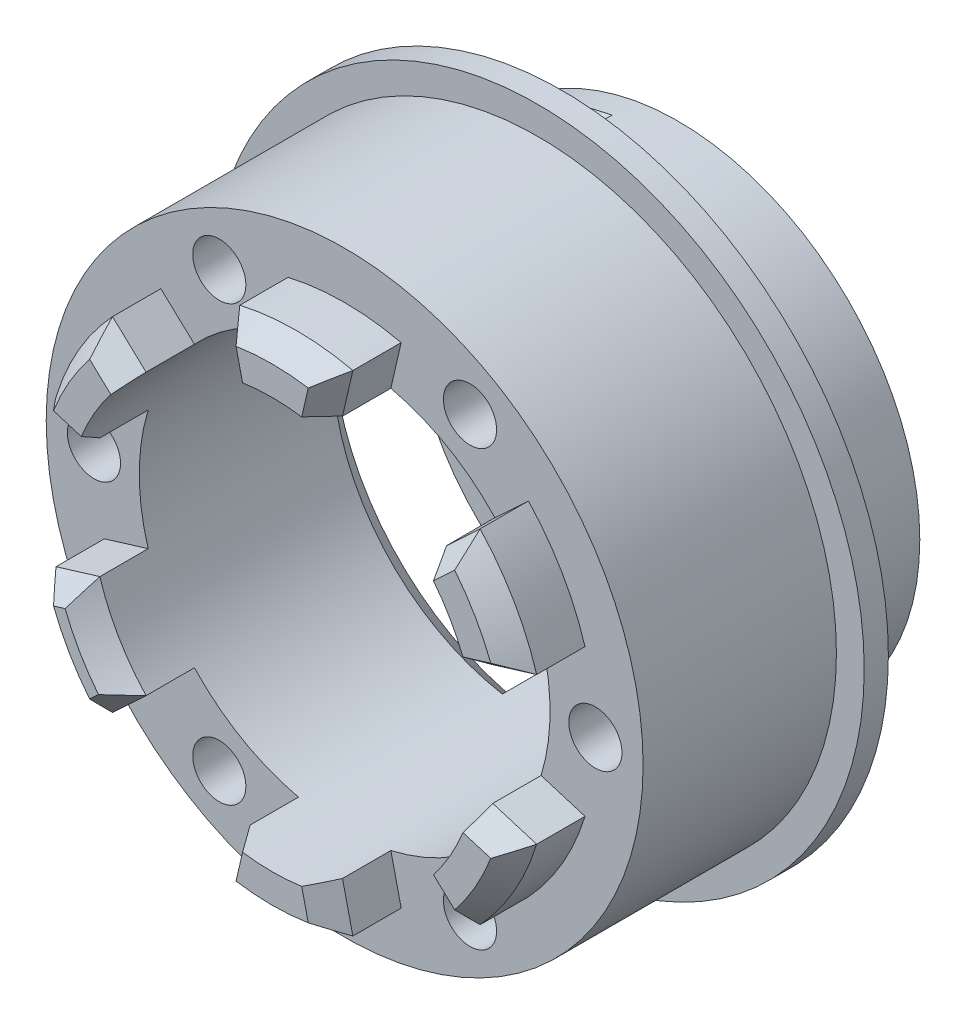
SolidWorks part; units mm, degrees
ref_plane "정면" through (0, 0, 0) normal (0, 0, 1) x (1, 0, 0)
ref_plane "윗면" through (0, 0, 0) normal (0, 1, 0) x (1, 0, 0)
ref_plane "우측면" through (0, 0, 0) normal (1, 0, 0) x (0, 0, -1)
sketch "스케치1" plane through (0, 0, 0) normal (0, 0, 1) x (1, 0, 0)
  circle A0 centre (0, 0) radius 10
  dimension "D1" = 20
extrude "보스-돌출1" add sketch "스케치1" along normal blind 2
sketch "스케치2" plane through (0, 0, 2) normal (0, 0, 1) x (1, 0, 0)
  circle A0 centre (0, 0) radius 10
  circle A1 centre (0, 0) radius 8.5
  circle A5 centre (0, 0) radius 10 construction
  dimension "D1" = 1.5
extrude "보스-돌출2" add sketch "스케치2" along normal blind 2.8
sketch "스케치4" plane through (0, 0, 4.8) normal (0, 0, 1) x (1, 0, 0)
  circle A0 centre (0, 0) radius 13.5
  circle A1 centre (0, 0) radius 8.5
  circle A2 centre (0, 0) radius 8.5 construction
  dimension "D1" = 27
extrude "보스-돌출3" add sketch "스케치4" along normal blind 1
sketch "스케치5" plane through (0, 0, 5.8) normal (0, 0, 1) x (1, 0, 0)
  circle A0 centre (0, 0) radius 8.5
  circle A1 centre (0, 0) radius 12.35
  circle A2 centre (0, 0) radius 8.5 construction
  dimension "D1" = 24.7
extrude "보스-돌출4" add sketch "스케치5" along normal blind 8
sketch "스케치6" plane through (0, 0, 13.8) normal (0, 0, 1) x (1, 0, 0)
  circle A0 centre (0, 0) radius 10.375 construction
  circle A6 centre (0, 0) radius 8.5 construction
  circle A8 centre (10.375, 0) radius 1.1
  circle A9 centre (5.1875, -8.985) radius 1.1
  circle A10 centre (-5.1875, -8.985) radius 1.1
  circle A11 centre (-10.375, 0) radius 1.1
  circle A12 centre (-5.1875, 8.985) radius 1.1
  circle A13 centre (5.1875, 8.985) radius 1.1
  point P19 (0, 0)
  point P20 (0, 0)
  dimension "D1" = 1.875
  dimension "D2" = 2.2
  dimension "D3" = 6
extrude "컷-돌출1" cut sketch "스케치6" against normal blind 8
sketch "스케치7" plane through (0, 0, 0) normal (0, 0, -1) x (-1, 0, 0)
  circle A0 centre (0, 0) radius 7 construction
  circle A5 centre (0, 0) radius 3
  circle A6 centre (-7, 0) radius 1.15
  circle A7 centre (7, 0) radius 1.15
  circle A9 centre (0, 7) radius 1.15
  circle A11 centre (0, -7) radius 1.15
  dimension "D1" = 14
  dimension "D2" = 2.3
  dimension "D4" = 6
extrude "컷-돌출2" cut sketch "스케치7" against normal through all
sketch "스케치10" plane through (0, 0, 13.8) normal (0, 0, 1) x (1, 0, 0)
  line L24 (2.3395, 10.1334) -> (1.9121, 8.2821)
  line L25 (-2.3395, 10.1334) -> (-1.9121, 8.2821)
  line L26 (7.6061, 7.0928) -> (6.2165, 5.797)
  line L27 (9.9456, 3.0407) -> (8.1286, 2.4852)
  line L28 (9.9456, -3.0407) -> (8.1286, -2.4852)
  line L29 (7.6061, -7.0928) -> (6.2165, -5.797)
  line L30 (2.3395, -10.1334) -> (1.9121, -8.2821)
  line L31 (-2.3395, -10.1334) -> (-1.9121, -8.2821)
  line L32 (-7.6061, -7.0928) -> (-6.2165, -5.797)
  line L33 (-9.9456, -3.0407) -> (-8.1286, -2.4852)
  line L34 (-9.9456, 3.0407) -> (-8.1286, 2.4852)
  line L35 (-7.6061, 7.0928) -> (-6.2165, 5.797)
  arc A0 (-7.6061, 7.0928) -> (-9.9456, 3.0407) centre (0, 0) ccw
  arc A1 (-8.1286, -2.4852) -> (-6.2165, -5.797) centre (0, 0) ccw
  arc A2 (2.3395, 10.1334) -> (-2.3395, 10.1334) centre (0, 0) ccw
  arc A3 (9.9456, 3.0407) -> (7.6061, 7.0928) centre (0, 0) ccw
  arc A4 (7.6061, -7.0928) -> (9.9456, -3.0407) centre (0, 0) ccw
  arc A5 (-2.3395, -10.1334) -> (2.3395, -10.1334) centre (0, 0) ccw
  arc A6 (-9.9456, -3.0407) -> (-7.6061, -7.0928) centre (0, 0) ccw
  arc A7 (-1.9121, -8.2821) -> (1.9121, -8.2821) centre (0, 0) ccw
  arc A8 (6.2165, -5.797) -> (8.1286, -2.4852) centre (0, 0) ccw
  arc A9 (8.1286, 2.4852) -> (6.2165, 5.797) centre (0, 0) ccw
  arc A10 (1.9121, 8.2821) -> (-1.9121, 8.2821) centre (0, 0) ccw
  arc A11 (-6.2165, 5.797) -> (-8.1286, 2.4852) centre (0, 0) ccw
  circle A12 centre (0, 0) radius 8.5 construction
  circle A13 centre (0, 0) radius 8.5 construction
  point P9 (0, 0)
  point P10 (0, 0)
  point P21 (0, 0)
  point P30 (0, 0)
  point P48 (0, 0)
  point P61 (0, 0)
  dimension "D1" = 1.9
  dimension "D4" = 6
extrude "보스-돌출5" add sketch "스케치10" along normal blind 3
chamfer "모따기1" distance 1 angle 35 19 edges at (-9.0067, -5.2, 16.8) (0, -10.4, 16.8) (9.0067, -5.2, 16.8) (9.0067, 5.2, 16.8) (0, 10.4, 16.8) (-9.0067, 5.2, 16.8) (-9.0371, -2.7629, 16.8) (-7.3612, -4.25, 16.8) (-6.9113, -6.4449, 16.8) (2.1258, -9.2078, 16.8) (-2.1258, -9.2078, 16.8) (6.9113, -6.4449, 16.8) (9.0371, -2.7629, 16.8) (9.0371, 2.7629, 16.8) (6.9113, 6.4449, 16.8) (2.1258, 9.2078, 16.8) (-2.1258, 9.2078, 16.8) (-9.0371, 2.7629, 16.8) (-6.9113, 6.4449, 16.8)
sketch "스케치11" plane through (0, 0, 0) normal (0, 0, -1) x (-1, 0, 0)
  line L0 (0, 0) -> (1.7365, 9.8481)
  line L1 (0, 0) -> (1.7365, -9.8481)
  line L2 (0, 0) -> (10, 0) construction
  circle A0 centre (0, 0) radius 10
  circle M6 centre (7, 0) radius 1.15
  circle M9 centre (0, 0) radius 3
  circle M10 centre (0, 0) radius 10
  dimension "D1" = 80
  dimension "D2" = 80
extrude "컷-돌출3" cut sketch "스케치11" against normal blind 2.8 from offset 2 contours L2 A0 L0 M9 M6 | L2 L1 M9 M10 M6 offset against normal yes
chamfer "모따기2" distance 1 angle 45 2 edges at (-8.5, 0, 4.8) (-10, 0, 2)
